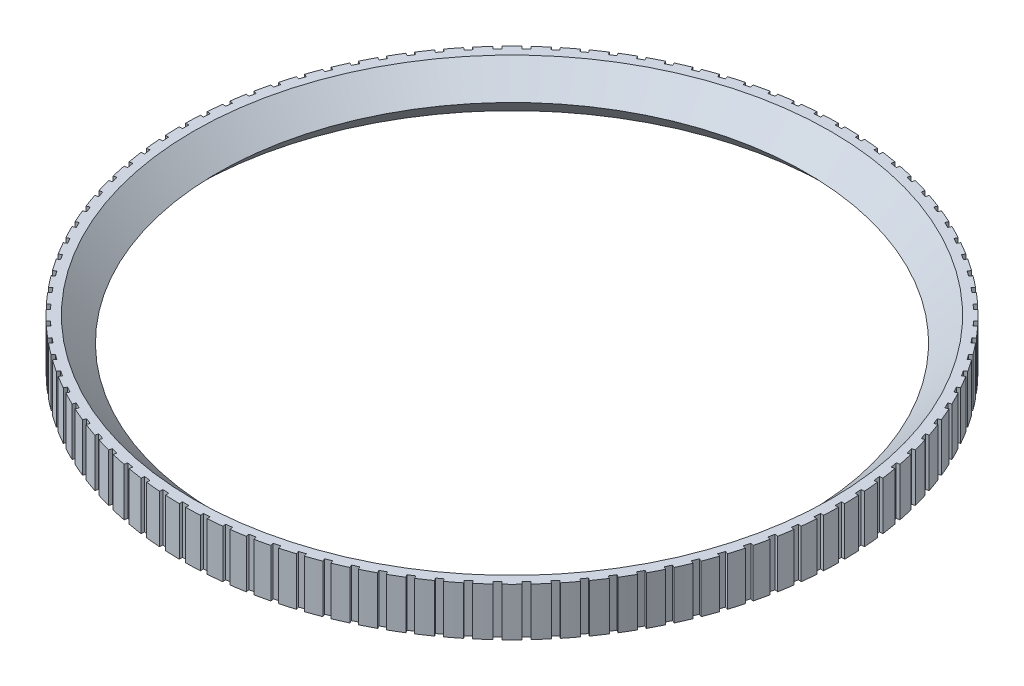
SolidWorks part; units mm, degrees
ref_plane "Front Plane" through (0, 0, 0) normal (0, 0, 1) x (1, 0, 0)
ref_plane "Top Plane" through (0, 0, 0) normal (0, 1, 0) x (1, 0, 0)
ref_plane "Right Plane" through (0, 0, 0) normal (1, 0, 0) x (0, 0, -1)
sketch "Sketch1" plane through (0, 0, 0) normal (1, 0, 0) x (0, 0, -1)
  line L0 (-46.23, 0) -> (-50.23, -4) construction
  line L1 (0, 0) -> (-46.23, 0) construction
  line L2 (-46.23, -4) -> (-50.23, -4) construction
  line L3 (-46.23, 4) -> (-46.23, -4) construction
  line L4 (-46.23, 4) -> (-50.23, 4) construction
  line L5 (-46.23, 0) -> (-50.23, 4) construction
  line L6 (-50.23, 4) -> (-52.23, 4) construction
  line L7 (-52.23, 4) -> (-52.23, -4) construction
  line L8 (-52.23, -4) -> (-50.23, -4) construction
  line L9 (-52.03, 3.8) -> (-52.03, -3.8)
  line L10 (-52.03, -3.8) -> (-50.3128, -3.8)
  line L11 (-46.5128, 0) -> (-50.3128, -3.8)
  line L12 (-46.5128, 0) -> (-50.3128, 3.8)
  line L13 (-50.3128, 3.8) -> (-52.03, 3.8)
  line L14 (0, 0) -> (0, -9.8677) construction
  dimension "D1" = 45
  dimension "D2" = 2
  dimension "D3" = 45
  dimension "D4" = 8
  dimension "D5" = 46.23
  dimension "D6" = 0.2
revolve "Revolve1" add sketch "Sketch1" angle 360 about L14
sketch "Sketch2" plane through (0, -3.8, 0) normal (0, -1, 0) x (1, 0, 0)
  line L0 (0, 0) -> (0, -52.03) construction
  line L2 (-0.5, -52.53) -> (0.5, -52.53)
  line L3 (-0.5, -52.53) -> (-0.5, -51.53)
  line L4 (-0.5, -51.53) -> (0.5, -51.53)
  line L5 (0.5, -52.53) -> (0.5, -51.53)
  line L6 (-0.5, -52.53) -> (0.5, -51.53) construction
  line L7 (-0.5, -51.53) -> (0.5, -52.53) construction
  circle A1 centre (0, 0) radius 52.03 construction
  dimension "D1" = 1
  dimension "D2" = 1
extrude "Cut-Extrude1" cut sketch "Sketch2" against normal through all
pattern_circular "CirPattern1" count 100 over 360 about axis through (0, 0, 0) along (0, 1, 0) of "Cut-Extrude1"
